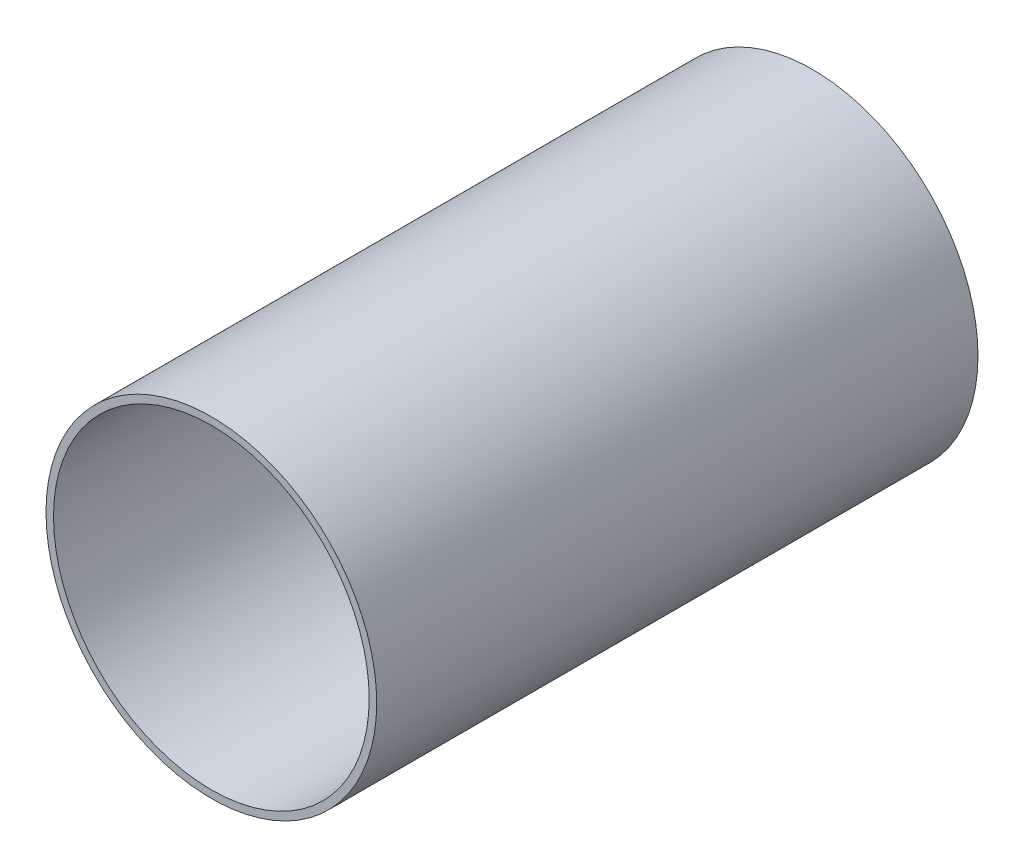
SolidWorks part; units mm, degrees
ref_plane "Front Plane" through (0, 0, 0) normal (0, 0, 1) x (1, 0, 0)
ref_plane "Top Plane" through (0, 0, 0) normal (0, 1, 0) x (1, 0, 0)
ref_plane "Right Plane" through (0, 0, 0) normal (1, 0, 0) x (0, 0, -1)
sketch "Sketch2" plane through (0, 0, 0) normal (0, 0, 1) x (1, 0, 0)
  circle A0 centre (0, 0) radius 52.5
  circle A1 centre (0, 0) radius 55
  dimension "D1" = 105
  dimension "D2" = 110
extrude "Boss-Extrude1" add sketch "Sketch2" along normal blind 200
